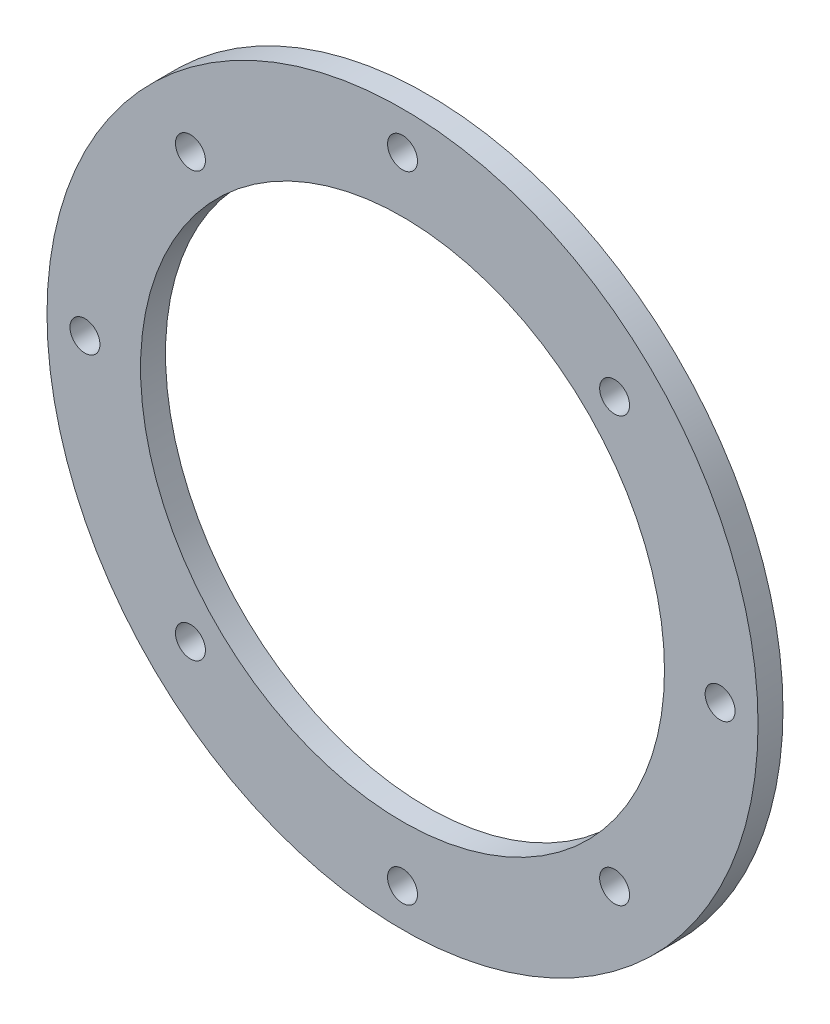
SolidWorks part; units mm, degrees
ref_plane "정면" through (0, 0, 0) normal (0, 0, 1) x (1, 0, 0)
ref_plane "윗면" through (0, 0, 0) normal (0, 1, 0) x (1, 0, 0)
ref_plane "우측면" through (0, 0, 0) normal (1, 0, 0) x (0, 0, -1)
sketch "스케치1" plane through (0, 0, 0) normal (0, 0, 1) x (1, 0, 0)
  circle A0 centre (0, 0) radius 28.5
  circle A2 centre (0, 0) radius 21
  dimension "D1" = 57
  dimension "D2" = 42
extrude "보스-돌출1" add sketch "스케치1" along normal blind 2
sketch "스케치2" plane through (0, 0, 0) normal (0, 0, 1) x (1, 0, 0)
  line L0 (0, 25.4558) -> (0, -25.4558) construction
  line L1 (-25.4558, 0) -> (25.4558, 0) construction
  circle A0 centre (0, 25.4558) radius 1.2
  circle A1 centre (25.4558, 0) radius 1.2
  circle A2 centre (-25.4558, 0) radius 1.2
  circle A3 centre (0, -25.4558) radius 1.2
  point P2 (0, 24.9018)
  point P4 (24.342, 0)
  point P8 (-25.8005, 0)
  dimension "D3" = 2.4
  dimension "D1" = 36
extrude "컷-돌출1" cut sketch "스케치2" along normal through all
sketch "스케치3" plane through (0, 0, 2) normal (0, 0, 1) x (1, 0, 0)
  line L0 (-17, 17) -> (17, -17) construction
  line L1 (17, 17) -> (-17, -17) construction
  point P0 (-17, 17)
  point P1 (17, 17)
  point P2 (17, -17)
  point P3 (-17, -17)
  point P8 (0, 0)
  point P9 (0, 0)
  dimension "D1" = 34
  dimension "D2" = 34
hole_wizard "M2 여유 구멍1" positions "3D스케치1" profile "스케치4" hole size "M2" standard "Ansi Metric" end condition through all
sketch3d "3D스케치1"
  point P0 (-17, 17, 2)
  point P3 (17, 17, 2)
  point P6 (17, -17, 2)
  point P9 (-17, -17, 2)
sketch "스케치4" plane through (-17, 17, 2) normal (1, 0, 0) x (0, -1, 0)
  line L0 (0, 0) -> (0, 2)
  line L1 (0, 2) -> (1.2, 2)
  line L2 (1.2, 2) -> (1.2, 0)
  line L5 (1.2, 0) -> (0, 0)
  line L11 (0, -6.35) -> (0, 107.95) construction
  dimension "관통 구멍 지름" = 2.4
  dimension "관통 구멍 깊이" = 2
